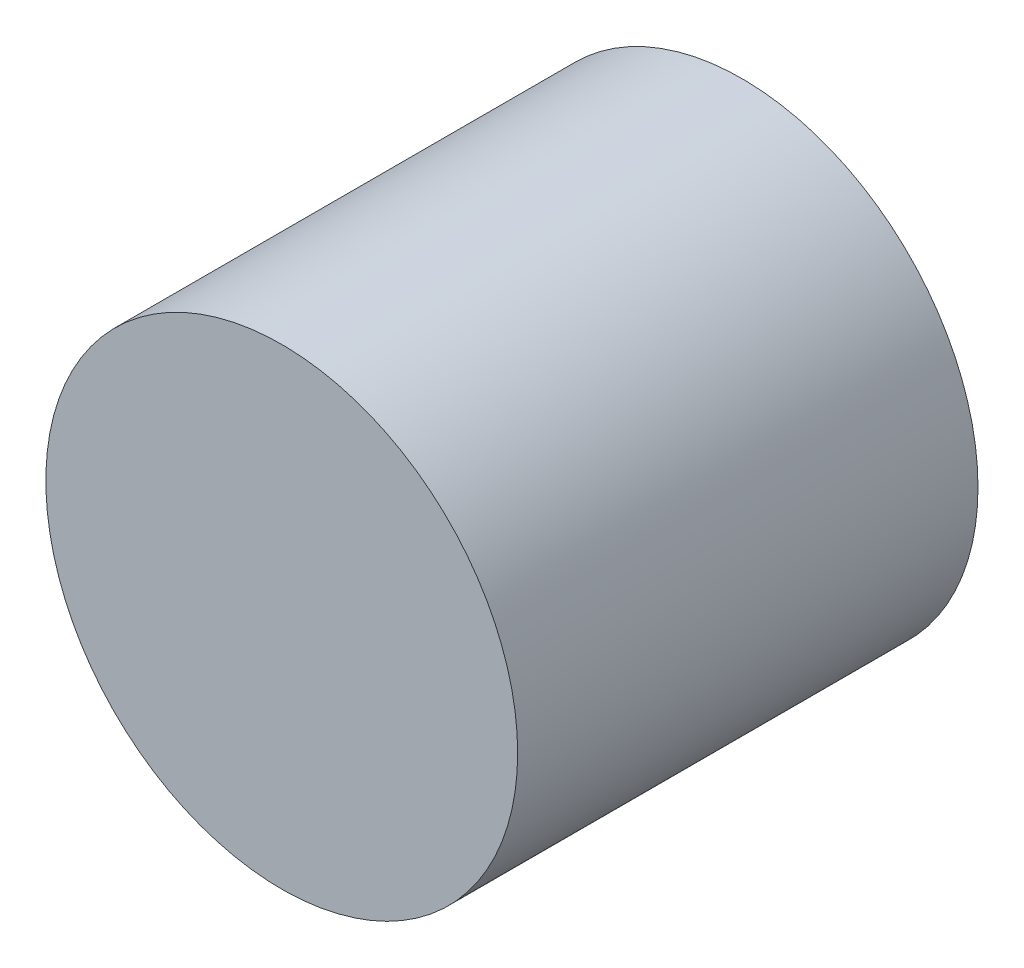
SolidWorks part; units mm, degrees
ref_plane "前视基准面" through (0, 0, 0) normal (0, 0, 1) x (1, 0, 0)
ref_plane "上视基准面" through (0, 0, 0) normal (0, 1, 0) x (1, 0, 0)
ref_plane "右视基准面" through (0, 0, 0) normal (1, 0, 0) x (0, 0, -1)
other "Configuration Table"
sketch "草图1" plane through (0, 0, 0) normal (0, 0, 1) x (1, 0, 0)
  circle A0 centre (0, 0) radius 50
extrude "凸台-拉伸1" add sketch "草图1" along normal blind 8
sketch "草图2" plane through (0, 0, 8) normal (0, 0, 1) x (1, 0, 0)
  line L0 (-4.6915, 2) -> (4.6915, 2)
  arc A0 (4.6915, 2) -> (-4.6915, 2) centre (0, 0) cw
sketch "草图3" plane through (0, 0, 8) normal (0, 0, 1) x (1, 0, 0)
  circle A0 centre (35, 0) radius 4.1
extrude "切除-拉伸2" cut sketch "草图3" against normal through all flip side to cut
